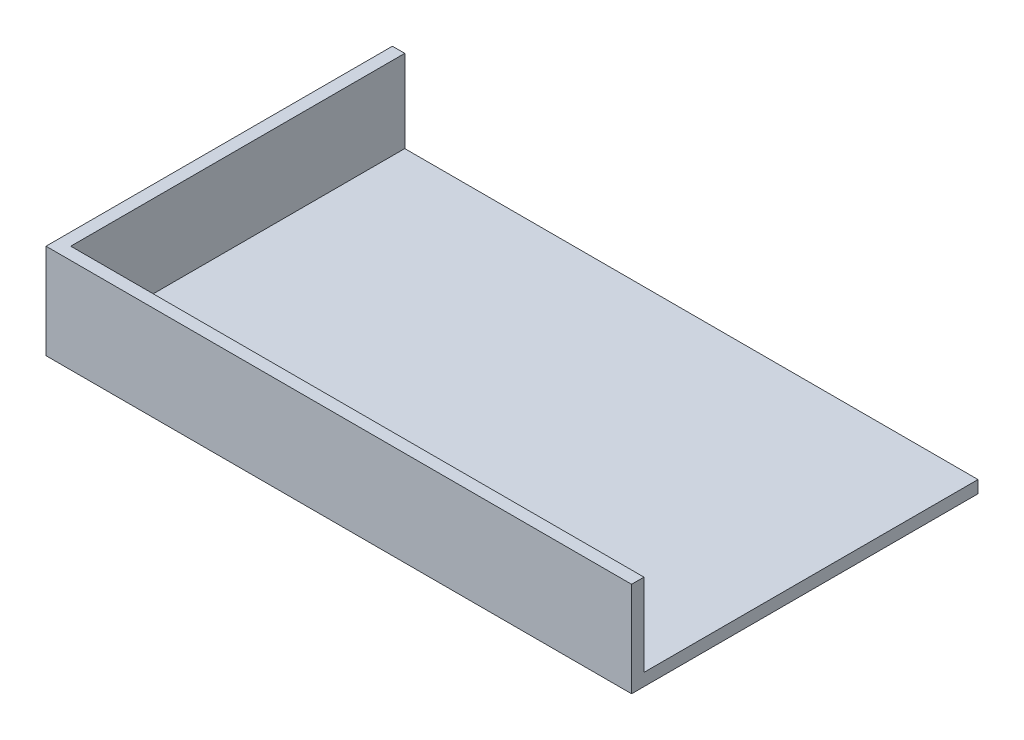
SolidWorks part; units mm, degrees
ref_plane "Front Plane" through (0, 0, 0) normal (0, 0, 1) x (1, 0, 0)
ref_plane "Top Plane" through (0, 0, 0) normal (0, 1, 0) x (1, 0, 0)
ref_plane "Right Plane" through (0, 0, 0) normal (1, 0, 0) x (0, 0, -1)
sketch "Sketch2" plane through (0, 0, 0) normal (0, 1, 0) x (1, 0, 0)
  line L1 (0, 0) -> (142, 0)
  line L2 (0, 0) -> (0, -84)
  line L3 (0, -84) -> (142, -84)
  line L4 (142, 0) -> (142, -84)
  dimension "D1" = 142
  dimension "D2" = 84
extrude "Boss-Extrude1" add sketch "Sketch2" along normal blind 3
sketch "Sketch3" plane through (0, 3, 0) normal (0, 1, 0) x (1, 0, 0)
  line L0 (142, -84) -> (142, 0) construction
  line L1 (0, -84) -> (142, -84)
  line L2 (0, -84) -> (0, -81)
  line L3 (0, -81) -> (142, -81)
  line L4 (142, -84) -> (142, -81)
  dimension "D1" = 3
extrude "Boss-Extrude2" add sketch "Sketch3" along normal blind 20
sketch "Sketch4" plane through (0, 3, 0) normal (0, 1, 0) x (1, 0, 0)
  line L1 (0, 0) -> (3, 0)
  line L2 (0, 0) -> (0, -81)
  line L3 (0, -81) -> (3, -81)
  line L4 (3, 0) -> (3, -81)
  dimension "D1" = 3
extrude "Boss-Extrude3" add sketch "Sketch4" along normal blind 20
